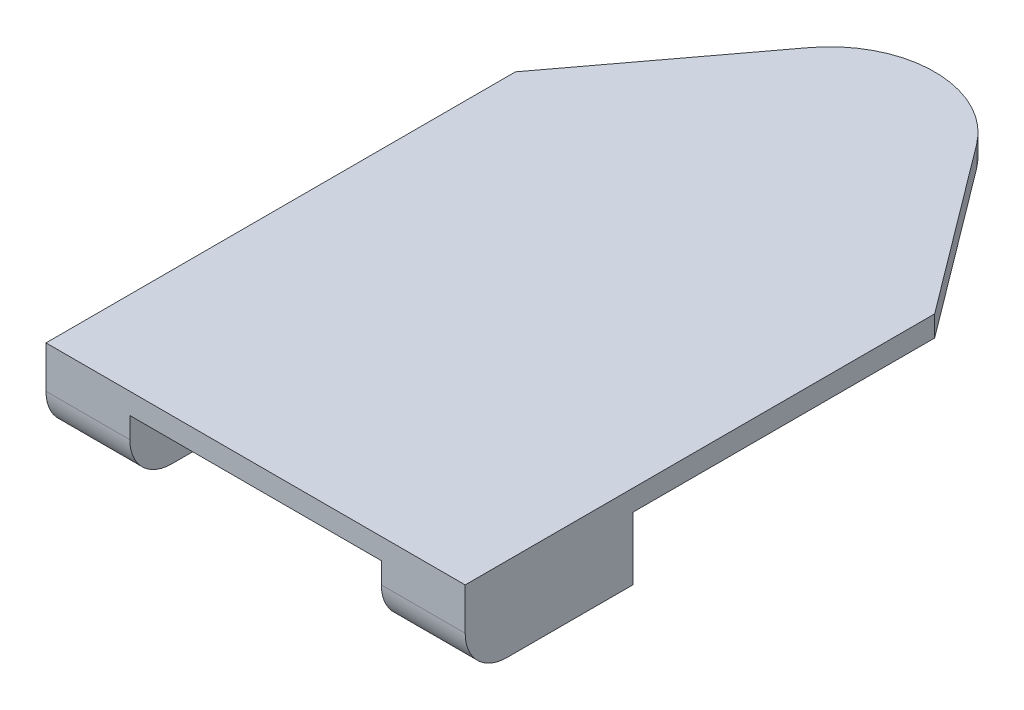
SolidWorks part; units mm, degrees
ref_plane "前视基准面" through (0, 0, 0) normal (0, 0, 1) x (1, 0, 0)
ref_plane "上视基准面" through (0, 0, 0) normal (0, 1, 0) x (1, 0, 0)
ref_plane "右视基准面" through (0, 0, 0) normal (1, 0, 0) x (0, 0, -1)
other "Configuration Table"
sketch "草图1" plane through (0, 0, 0) normal (0, 1, 0) x (1, 0, 0)
  line L0 (0, 0) -> (100, 0)
  line L5 (100, 0) -> (100, 112)
  line L6 (100, 112) -> (70, 152)
  line L12 (30, 152) -> (0, 112)
  line L13 (0, 112) -> (0, 0)
  arc A0 (30, 152) -> (70, 152) centre (50, 137) cw
  dimension "D4" = 137
  dimension "D7" = 25
  dimension "D1" = 112
  dimension "D2" = 100
  dimension "D3" = 40
  dimension "D5" = 30
  dimension "D6" = 40
extrude "凸台-拉伸1" add sketch "草图1" along normal blind 5
sketch "草图2" plane through (0, 0, 0) normal (0, -1, 0) x (1, 0, 0)
  line L1 (100, 0) -> (80, 0)
  line L2 (100, 0) -> (100, -40)
  line L3 (100, -40) -> (80, -40)
  line L4 (80, 0) -> (80, -40)
  line L5 (0, 0) -> (20, 0)
  line L6 (0, 0) -> (0, -40)
  line L7 (0, -40) -> (20, -40)
  line L8 (20, 0) -> (20, -40)
  dimension "D1" = 20
  dimension "D2" = 40
extrude "凸台-拉伸3" add sketch "草图2" along normal blind 15
fillet "圆角1" radius 10 2 edges at (90, -15, 0) (10, -15, 0)
